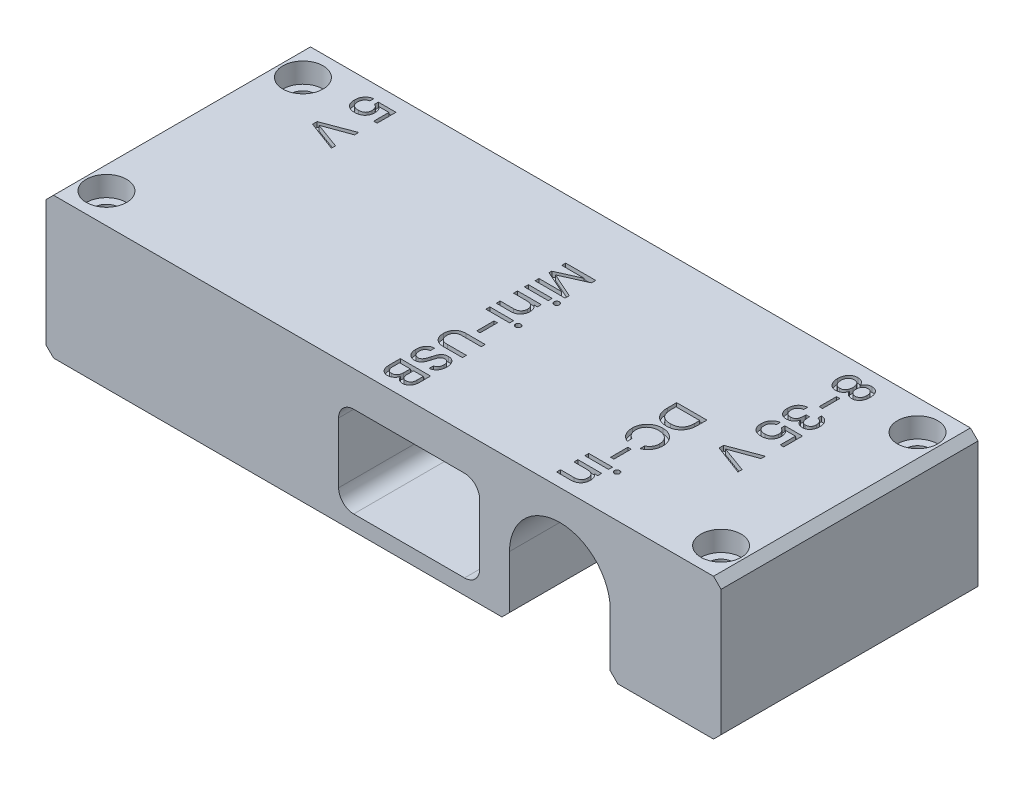
SolidWorks part; units mm, degrees
ref_plane "Front Plane" through (0, 0, 0) normal (0, 0, 1) x (1, 0, 0)
ref_plane "Top Plane" through (0, 0, 0) normal (0, 1, 0) x (1, 0, 0)
ref_plane "Right Plane" through (0, 0, 0) normal (1, 0, 0) x (0, 0, -1)
sketch "Sketch1" plane through (0, 0, 0) normal (0, 1, 0) x (1, 0, 0)
  line L1 (0, 0) -> (67, 0)
  line L2 (0, 0) -> (0, 25.5)
  line L3 (0, 25.5) -> (67, 25.5)
  line L4 (67, 0) -> (67, 25.5)
  dimension "D1" = 67
  dimension "D2" = 25.5
extrude "Boss-Extrude1" add sketch "Sketch1" along normal blind 14 contours L2 L1 L4 L3
sketch "Sketch2" plane through (0, 0, 0) normal (0, 0, 1) x (1, 0, 0)
  line L1 (0, 0) -> (67, 0) construction
  line L2 (67, 14) -> (67, 0) construction
  line L3 (44, 12) -> (58, 12) construction
  line L4 (44, 12) -> (44, 0) construction
  line L5 (44, 0) -> (58, 0) construction
  line L6 (58, 12) -> (58, 0) construction
  line L7 (44, 12) -> (58, 0) construction
  line L8 (44, 0) -> (58, 12) construction
  line L9 (46, 6) -> (46, 0)
  line L10 (46, 0) -> (56, 0)
  line L11 (56, 0) -> (56, 6)
  arc A0 (56, 6) -> (46, 6) centre (51, 6) ccw
  dimension "D1" = 1
  dimension "D2" = 10
  dimension "D3" = 14
  dimension "D4" = 12
  dimension "D5" = 9
extrude "Cut-Extrude1" cut sketch "Sketch2" against normal blind 12.5
sketch "Sketch3" plane through (0, 0, 0) normal (0, -1, 0) x (1, 0, 0)
  line L0 (0, -25.5) -> (67, -25.5) construction
  line L1 (44, -25.5) -> (58, -25.5)
  line L2 (44, -25.5) -> (44, -12.5)
  line L3 (44, -12.5) -> (58, -12.5)
  line L4 (58, -25.5) -> (58, -12.5)
  line L7 (46, -12.5) -> (56, -12.5) construction
  line L9 (56, 0) -> (46, 0) construction
  point P12 (51, 0)
  dimension "D1" = 14
  dimension "D2" = 7
extrude "Cut-Extrude2" cut sketch "Sketch3" against normal blind 12
sketch "Sketch5" plane through (0, 0, 0) normal (0, 0, 1) x (1, 0, 0)
  line L0 (33.5, 14) -> (33.5, 0) construction
  line L1 (0, 14) -> (67, 14) construction
  line L2 (0, 0) -> (46, 0) construction
  line L4 (30.54, 10.5) -> (41.54, 10.5)
  line L5 (29.04, 9) -> (29.04, 3)
  line L6 (30.54, 1.5) -> (41.54, 1.5)
  line L7 (43.04, 9) -> (43.04, 3)
  line L8 (29.04, 10.5) -> (43.04, 1.5) construction
  line L9 (29.04, 1.5) -> (43.04, 10.5) construction
  arc A0 (43.04, 9) -> (41.54, 10.5) centre (41.54, 9) ccw
  arc A1 (29.04, 3) -> (30.54, 1.5) centre (30.54, 3) ccw
  arc A2 (30.54, 10.5) -> (29.04, 9) centre (30.54, 9) ccw
  arc A3 (41.54, 1.5) -> (43.04, 3) centre (41.54, 3) ccw
  point P6 (36.04, 6)
  point P23 (0, 0)
  point P24 (32.3737, 6)
  point P25 (36.4934, 6)
  dimension "D4" = 1.5
  dimension "D1" = 6
  dimension "D2" = 14
  dimension "D3" = 9
  dimension "D5" = 2.54
extrude "Cut-Extrude3" cut sketch "Sketch5" against normal through all
sketch "Sketch6" plane through (0, 14, 0) normal (0, 1, 0) x (1, 0, 0)
  line L0 (3, 25.5) -> (3, 0) construction
  line L1 (0, 25.5) -> (67, 25.5) construction
  line L2 (0, 0) -> (67, 0) construction
  line L3 (64, 25.5) -> (64, 0) construction
  line L4 (0, 0) -> (0, 25.5) construction
  line L5 (67, 0) -> (67, 25.5) construction
  circle A0 centre (3, 22.5) radius 2
  circle A1 centre (64, 22.5) radius 2
  circle A2 centre (64, 3) radius 2
  circle A3 centre (3, 3) radius 2
  dimension "D3" = 4
  dimension "D5" = 4
  dimension "D6" = 4
  dimension "D7" = 4
  dimension "D8" = 3
  dimension "D1" = 3
  dimension "D2" = 3
  dimension "D4" = 3
extrude "Cut-Extrude4" cut sketch "Sketch6" against normal blind 2
sketch "Sketch7" plane through (0, 12, 0) normal (0, 1, 0) x (1, 0, 0)
  circle A0 centre (3, 22.5) radius 1.2
  circle A1 centre (64, 22.5) radius 1.2
  circle A2 centre (64, 3) radius 1.2
  circle A3 centre (3, 3) radius 1.2
  dimension "D1" = 2.4
  dimension "D2" = 2.4
  dimension "D3" = 2.4
  dimension "D4" = 2.4
extrude "Cut-Extrude5" cut sketch "Sketch7" against normal up to surface (12 mm away) up to face at (30, 0, -12.6667)
chamfer "Chamfer1" distance 0.75 angle 45 8 edges at (0, 14, -12.75) (0, 0, -12.75) (44, 0, -19) (46, 0, -6.25) (58, 0, -19) (56, 0, -6.25) (67, 0, -12.75) (67, 14, -12.75)
sketch "Sketch8" plane through (0, 14, 0) normal (0, 1, 0) x (1, 0, 0)
  line L0 (32, 19.9138) -> (32, 0) construction
  line L1 (49.5, 13.4254) -> (49.5, 0) construction
  line L2 (51, 0) -> (51, 21.08) construction
  line L3 (46, 0) -> (56, 0) construction
  line L5 (33.5, 0) -> (33.5, 20.2949) construction
  line L6 (0.75, 0) -> (66.25, 0) construction
  text T0 "Mini-USB" font "Poppins" height 3
  text T1 "DC-in" font "Poppins" height 3
  point P3 (49.5, 36.1185)
  point P4 (49.5, -0.2341)
  point P5 (49.5, 0)
  point P6 (49.5, 7.0874)
  point P8 (49.5, 9.9249)
  point P13 (49.5, 11.7816)
  point P14 (49.5, 12.7975)
  point P21 (0, 0)
  point P22 (32, 19.2433)
  point P23 (0, 0)
  point P24 (32, 19.3081)
  point P25 (32, 20.2949)
  point P26 (0, 0)
  point P27 (32, 19.9138)
  point P28 (49.5, 13.7936)
  point P29 (0, 0)
  point P30 (49.5, 13.3025)
  point P31 (49.5, 13.3402)
  point P32 (0, 0)
  point P33 (49.5, 13.4254)
  dimension "D1" = 1.5
  dimension "D2" = 1.5
extrude "Cut-Extrude6" cut sketch "Sketch8" against normal blind 0.5
sketch "Sketch9" plane through (0, 14, 0) normal (0, 1, 0) x (1, 0, 0)
  line L0 (55.5, 24.5) -> (55.5, 0) construction
  line L1 (0.75, 0) -> (66.25, 0) construction
  line L2 (0.75, 25.5) -> (66.25, 25.5) construction
  line L3 (67, 25.5) -> (67, 0) construction
  line L4 (7.5, 24.5) -> (7.5, 0) construction
  line L6 (0, 0) -> (0, 25.5) construction
  text T0 "8-35 V" font "Poppins" height 3
  text T1 "5 V" font "Poppins" height 3
  dimension "D1" = 11.5
  dimension "D2" = 7.5
  dimension "D3" = 1
  dimension "D4" = 1
extrude "Cut-Extrude7" cut sketch "Sketch9" against normal blind 0.5
